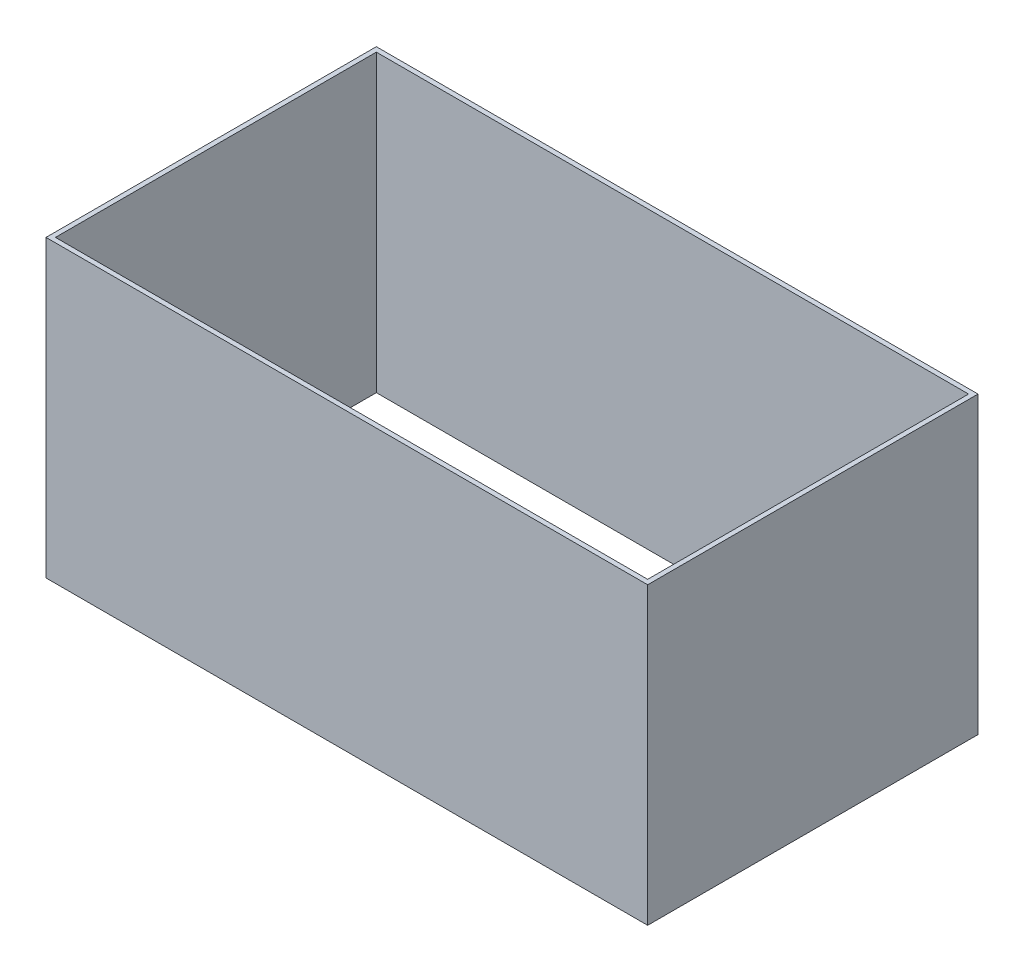
SolidWorks part; units mm, degrees
material "ABS"
ref_plane "Front Plane" through (0, 0, 0) normal (0, 0, 1) x (1, 0, 0)
ref_plane "Top Plane" through (0, 0, 0) normal (0, 1, 0) x (1, 0, 0)
ref_plane "Right Plane" through (0, 0, 0) normal (1, 0, 0) x (0, 0, -1)
sketch "Sketch1" plane through (0, 0, 0) normal (0, 1, 0) x (1, 0, 0)
  line L1 (-51, 28) -> (51, 28)
  line L2 (-51, 28) -> (-51, -28)
  line L3 (-51, -28) -> (51, -28)
  line L4 (51, 28) -> (51, -28)
  line L5 (-51, 28) -> (51, -28) construction
  line L6 (-51, -28) -> (51, 28) construction
  line L7 (-50.2, -27.2) -> (50.2, -27.2)
  line L8 (-50.2, -27.2) -> (-50.2, 27.2)
  line L9 (-50.2, 27.2) -> (50.2, 27.2)
  line L10 (50.2, -27.2) -> (50.2, 27.2)
  line L11 (-50.2, -27.2) -> (50.2, 27.2) construction
  line L12 (-50.2, 27.2) -> (50.2, -27.2) construction
  point P0 (0, 0)
  point P6 (0, 0)
  dimension "D1" = 56
  dimension "D2" = 102
  dimension "D3" = 0.8
  dimension "D4" = 0.8
extrude "WALLS" add sketch "Sketch1" along normal blind 50
sketch "Sketch3" plane through (-51, 0, 0) normal (-1, 0, 0) x (0, 0, 1)
  line L0 (-28, 50) -> (-28, 0) construction
  line L11 (-28, 0) -> (28, 0) construction
  line L12 (-15, 6) -> (-7, 6)
  line L13 (-15, 6) -> (-15, 0)
  line L14 (-15, 0) -> (-7, 0)
  line L15 (-7, 6) -> (-7, 0)
  dimension "D1" = 8
  dimension "D7" = 6
  dimension "D8" = 13
extrude "USB_HOLE" cut sketch "Sketch3" against normal up to next
